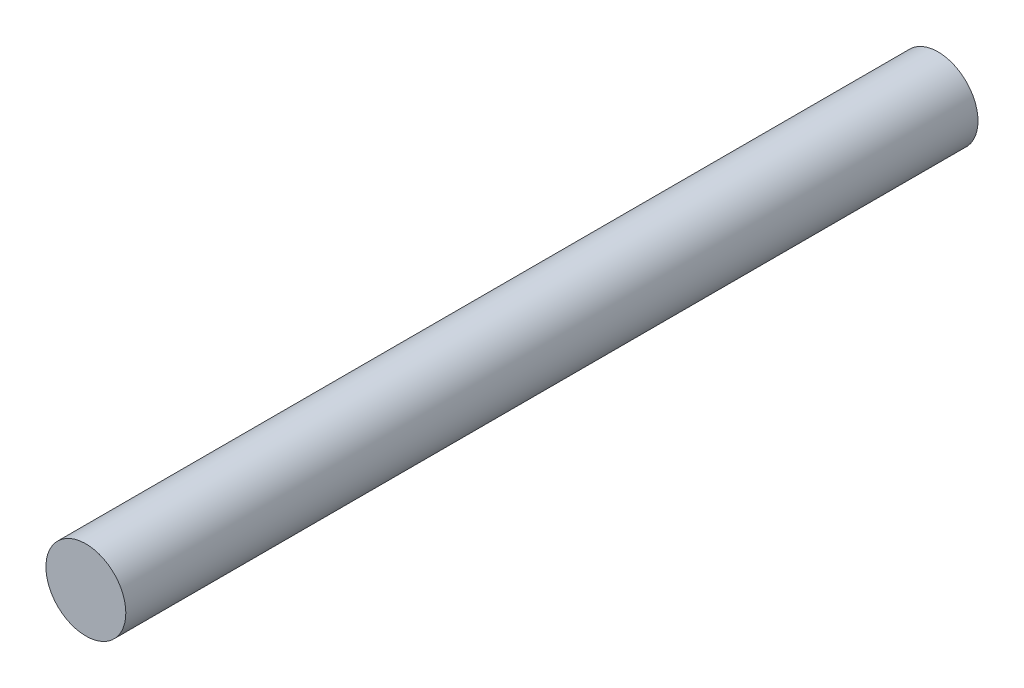
SolidWorks part; units mm, degrees
ref_plane "Alzado" through (0, 0, 0) normal (0, 0, 1) x (1, 0, 0)
ref_plane "Planta" through (0, 0, 0) normal (0, 1, 0) x (1, 0, 0)
ref_plane "Vista lateral" through (0, 0, 0) normal (1, 0, 0) x (0, 0, -1)
sketch "Croquis1" plane through (0, 0, 0) normal (0, 0, 1) x (1, 0, 0)
  circle A0 centre (0, 0) radius 9.525
  dimension "D1" = 19.05
extrude "Saliente-Extruir1" add sketch "Croquis1" along normal mid plane 203.2
